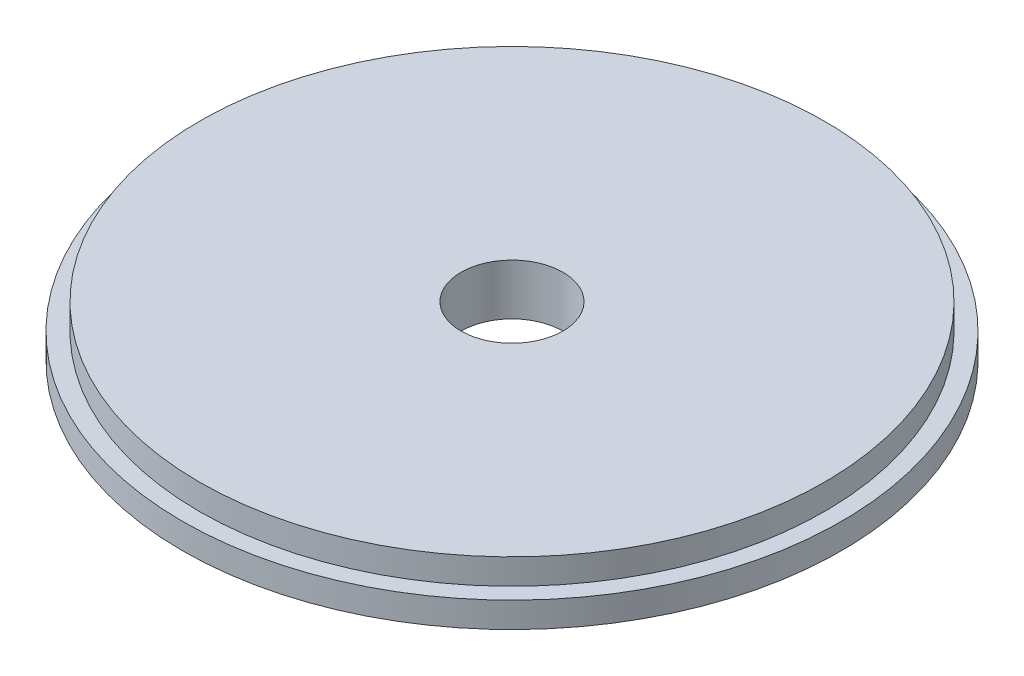
SolidWorks part; units mm, degrees
ref_plane "Front Plane" through (0, 0, 0) normal (0, 0, 1) x (1, 0, 0)
ref_plane "Top Plane" through (0, 0, 0) normal (0, 1, 0) x (1, 0, 0)
ref_plane "Right Plane" through (0, 0, 0) normal (1, 0, 0) x (0, 0, -1)
sketch "Sketch1" plane through (0, 0, 0) normal (0, 1, 0) x (1, 0, 0)
  circle A0 centre (0, 0) radius 19.4
  dimension "D1" = 38.8
extrude "Boss-Extrude1" add sketch "Sketch1" along normal blind 1.5
sketch "Sketch2" plane through (0, 1.5, 0) normal (0, 1, 0) x (1, 0, 0)
  circle A0 centre (0, 0) radius 18.4
  dimension "D1" = 36.8
extrude "Boss-Extrude2" add sketch "Sketch2" along normal blind 1.5
sketch "Sketch3" plane through (0, 3, 0) normal (0, 1, 0) x (1, 0, 0)
  circle A0 centre (0, 0) radius 3
  dimension "D1" = 6
extrude "Cut-Extrude1" cut sketch "Sketch3" against normal blind 3
